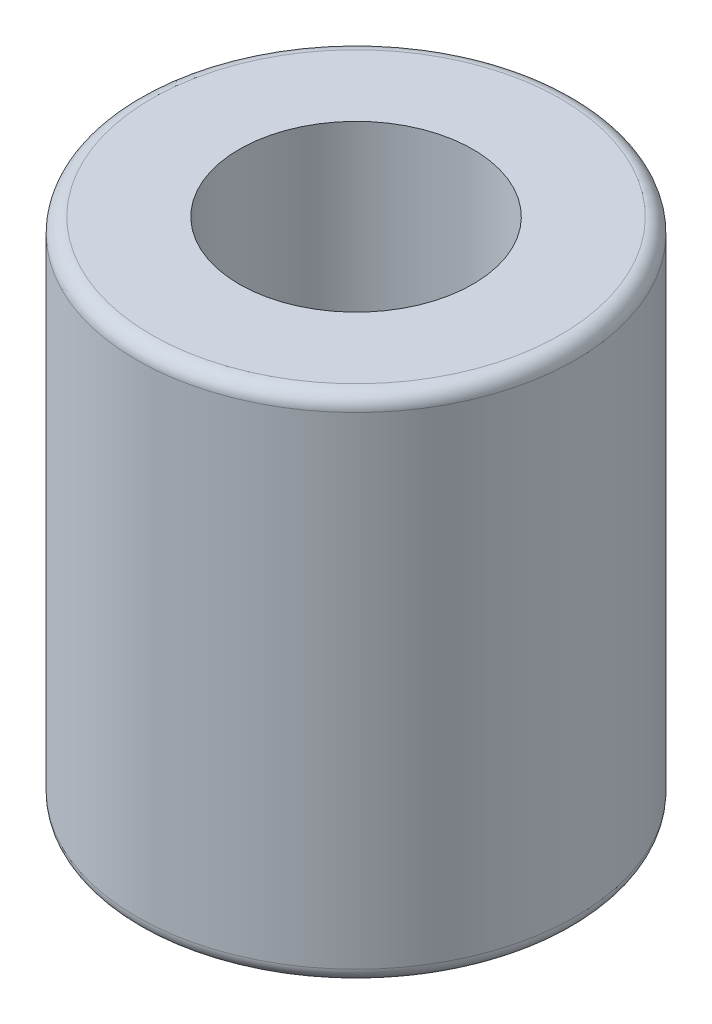
SolidWorks part; units mm, degrees
ref_plane "Front Plane" through (0, 0, 0) normal (0, 0, 1) x (1, 0, 0)
ref_plane "Top Plane" through (0, 0, 0) normal (0, 1, 0) x (1, 0, 0)
ref_plane "Right Plane" through (0, 0, 0) normal (1, 0, 0) x (0, 0, -1)
sketch "Sketch1" plane through (0, 0, 0) normal (0, 1, 0) x (1, 0, 0)
  circle A0 centre (0, 0) radius 3
  dimension "D1" = 6
extrude "Boss-Extrude1" add sketch "Sketch1" along normal blind 7
sketch "Sketch2" plane through (0, 7, 0) normal (0, 1, 0) x (1, 0, 0)
  circle A0 centre (0, 0) radius 1.6
  dimension "D1" = 3.2
extrude "Cut-Extrude1" cut sketch "Sketch2" against normal through all
fillet "Fillet1" radius 0.2 2 edges at (0, 0, 3) (0, 7, 3)
